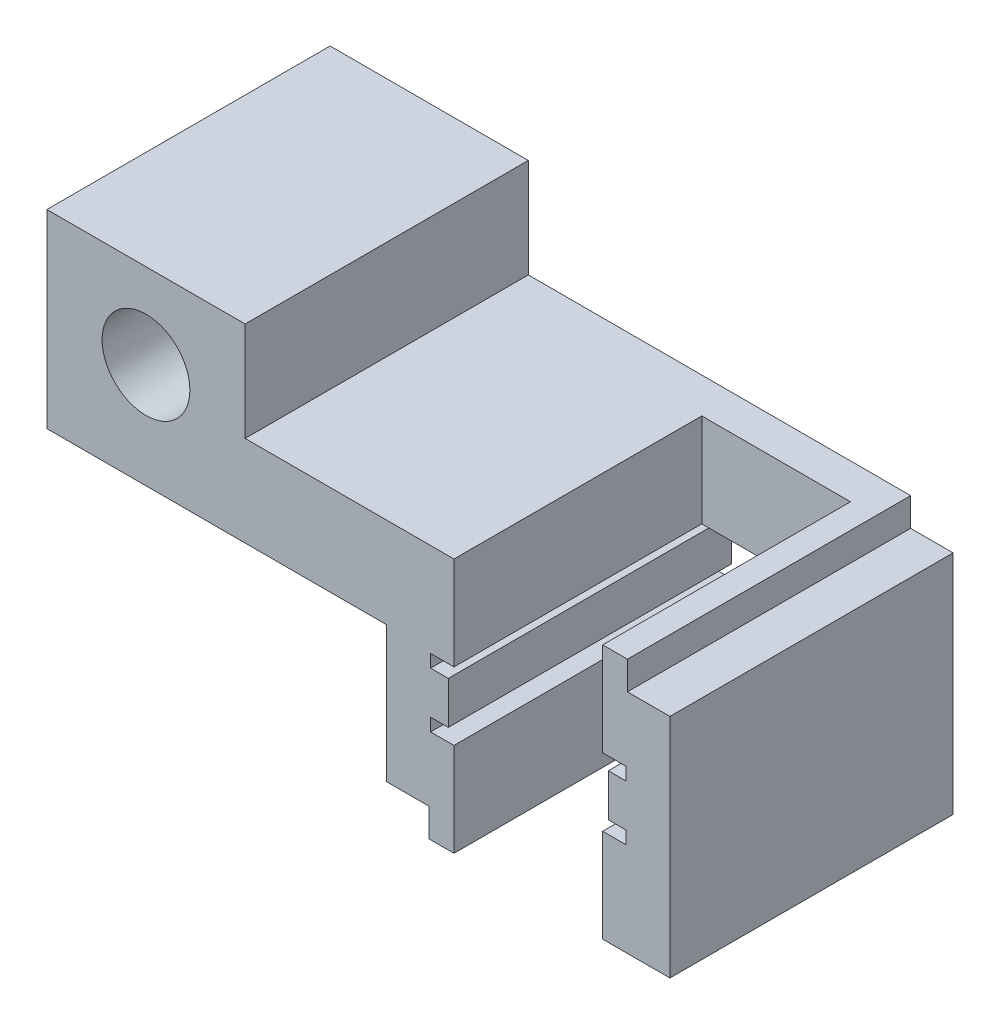
SolidWorks part; units mm, degrees
ref_plane "Front Plane" through (0, 0, 0) normal (0, 0, 1) x (1, 0, 0)
ref_plane "Top Plane" through (0, 0, 0) normal (0, 1, 0) x (1, 0, 0)
ref_plane "Right Plane" through (0, 0, 0) normal (1, 0, 0) x (0, 0, -1)
sketch "Sketch1" plane through (0, 0, 0) normal (0, 0, 1) x (1, 0, 0)
  line L1 (-9.5436, 2.8631) -> (10.4564, 2.8631)
  line L2 (-9.5436, 2.8631) -> (-9.5436, -0.1369)
  line L3 (-9.5436, -0.1369) -> (10.4564, -0.1369)
  line L4 (10.4564, 2.8631) -> (10.4564, -0.1369)
  dimension "D1" = 20
  dimension "D2" = 3
extrude "Boss-Extrude1" add sketch "Sketch1" against normal blind 20
sketch "Sketch2" plane through (0, 0, 0) normal (0, 0, 1) x (1, 0, 0)
  line L0 (0.4564, 2.8631) -> (0.4564, 1.802) construction
  line L1 (-5.1936, 2.8631) -> (6.1064, 2.8631)
  line L2 (-5.1936, 2.8631) -> (-5.1936, -0.1369)
  line L3 (-5.1936, -0.1369) -> (6.1064, -0.1369)
  line L4 (6.1064, 2.8631) -> (6.1064, -0.1369)
  line L5 (10.4564, 2.8631) -> (-9.5436, 2.8631) construction
  line L6 (-9.5436, -0.1369) -> (10.4564, -0.1369) construction
  point P8 (0.4564, 2.8631)
  dimension "D1" = 0
  dimension "D2" = 11.3
  dimension "D3" = 0
  dimension "D4" = 0
sketch "Sketch3" plane through (0, 0, 0) normal (0, 0, 1) x (1, 0, 0)
  line L0 (-9.5436, 2.8631) -> (-9.5436, -0.1369) construction
  line L1 (-9.5436, 10.3631) -> (10.4564, 10.3631)
  line L2 (-9.5436, 10.3631) -> (-9.5436, 2.8631)
  line L3 (-9.5436, 2.8631) -> (10.4564, 2.8631)
  line L4 (10.4564, 10.3631) -> (10.4564, 2.8631)
  dimension "D1" = 0
  dimension "D2" = 0
  dimension "D3" = 0
  dimension "D4" = 7.5
extrude "Boss-Extrude2" add sketch "Sketch3" against normal blind 20
sketch "Sketch4" plane through (0, 0, 0) normal (0, 0, 1) x (1, 0, 0)
  line L1 (-9.5436, -0.1369) -> (10.4564, -0.1369)
  line L2 (-9.5436, -0.1369) -> (-9.5436, -7.6369)
  line L3 (-9.5436, -7.6369) -> (10.4564, -7.6369)
  line L4 (10.4564, -0.1369) -> (10.4564, -7.6369)
  dimension "D1" = 0
  dimension "D2" = 0
  dimension "D3" = 0
  dimension "D4" = 7.5
extrude "Boss-Extrude3" add sketch "Sketch4" against normal blind 20
sketch "Sketch5" plane through (0, 0, 0) normal (0, 0, 1) x (1, 0, 0)
  line L0 (0.4564, -1.0369) -> (0.4564, -1.9441) construction
  line L1 (-6.4436, -0.1369) -> (7.3564, -0.1369)
  line L2 (-6.4436, -0.1369) -> (-6.4436, -1.0369)
  line L3 (-6.4436, -1.0369) -> (7.3564, -1.0369)
  line L4 (7.3564, -0.1369) -> (7.3564, -1.0369)
  line L5 (-5.1936, -0.1369) -> (6.1064, -0.1369) construction
  line L6 (0.4564, 3.7631) -> (0.4564, 5.897) construction
  line L7 (-6.4436, 3.7631) -> (7.3564, 3.7631)
  line L8 (-6.4436, 3.7631) -> (-6.4436, 2.8631)
  line L9 (-6.4436, 2.8631) -> (7.3564, 2.8631)
  line L10 (7.3564, 3.7631) -> (7.3564, 2.8631)
  line L11 (-5.1936, 2.8631) -> (6.1064, 2.8631) construction
  dimension "D1" = 0.9
  dimension "D2" = 13.8
  dimension "D3" = 0
  dimension "D4" = 0
  dimension "D5" = 13.8
  dimension "D6" = 0.9
  dimension "D7" = 0
  dimension "D8" = 0
sketch "Sketch6" plane through (0, 0, 0) normal (0, 0, 1) x (1, 0, 0)
  line L0 (10.4564, 10.3631) -> (-9.5436, 10.3631) construction
  line L1 (-4.7936, 10.3631) -> (5.7064, 10.3631)
  line L2 (-4.7936, 10.3631) -> (-4.7936, 3.7631)
  line L3 (-4.7936, 3.7631) -> (5.7064, 3.7631)
  line L4 (5.7064, 10.3631) -> (5.7064, 3.7631)
  line L5 (0.4564, 3.7631) -> (0.4564, 8.0136) construction
  line L6 (-6.4436, 3.7631) -> (7.3564, 3.7631) construction
  dimension "D1" = 10.5
  dimension "D2" = 0
  dimension "D3" = 0
  dimension "D4" = 0
sketch "Sketch7" plane through (0, 0, 0) normal (0, 0, 1) x (1, 0, 0)
  line L0 (0.4564, -7.6369) -> (0.4564, -4.6998) construction
  line L1 (-4.7936, -1.0369) -> (5.7064, -1.0369)
  line L2 (-4.7936, -1.0369) -> (-4.7936, -7.6369)
  line L3 (-4.7936, -7.6369) -> (5.7064, -7.6369)
  line L4 (5.7064, -1.0369) -> (5.7064, -7.6369)
  line L5 (-9.5436, -7.6369) -> (10.4564, -7.6369) construction
  line L6 (-6.4436, -1.0369) -> (7.3564, -1.0369) construction
  dimension "D1" = 10.5
  dimension "D2" = 0
  dimension "D3" = 0
  dimension "D4" = 0
extrude "Cut-Extrude1" cut sketch "Sketch2" against normal blind 20
extrude "Cut-Extrude2" cut sketch "Sketch5" against normal blind 20
extrude "Cut-Extrude3" cut sketch "Sketch6" against normal blind 17.5
extrude "Cut-Extrude4" cut sketch "Sketch7" against normal blind 17.5
sketch "Sketch8" plane through (0, 0, 0) normal (0, 0, 1) x (1, 0, 0)
  line L1 (10.4564, 10.3631) -> (7.4564, 10.3631)
  line L2 (10.4564, 10.3631) -> (10.4564, 8.3631)
  line L3 (10.4564, 8.3631) -> (7.4564, 8.3631)
  line L4 (7.4564, 10.3631) -> (7.4564, 8.3631)
  line L5 (-9.5436, -7.6369) -> (-6.5436, -7.6369)
  line L6 (-9.5436, -7.6369) -> (-9.5436, -5.6369)
  line L7 (-9.5436, -5.6369) -> (-6.5436, -5.6369)
  line L8 (-6.5436, -7.6369) -> (-6.5436, -5.6369)
  dimension "D1" = 2
  dimension "D2" = 3
  dimension "D3" = 2
  dimension "D4" = 3
extrude "Cut-Extrude5" cut sketch "Sketch8" against normal blind 20
sketch "Sketch9" plane through (-9.5436, 0, 0) normal (-1, 0, 0) x (0, 0, 1)
  line L0 (-20, 10.3631) -> (-20, -5.6369) construction
  line L1 (-20, 17.3631) -> (0, 17.3631)
  line L2 (-20, 17.3631) -> (-20, 3.9631)
  line L3 (-20, 3.9631) -> (0, 3.9631)
  line L4 (0, 17.3631) -> (0, 3.9631)
  line L5 (0, 10.3631) -> (0, -5.6369) construction
  line L6 (-20, 10.3631) -> (0, 10.3631) construction
  dimension "D1" = 13.4
  dimension "D2" = 0
  dimension "D3" = 0
  dimension "D4" = 6.4
extrude "Boss-Extrude4" add sketch "Sketch9" along normal blind 24
sketch "Sketch10" plane through (0, 0, 0) normal (0, 0, 1) x (1, 0, 0)
  circle A0 centre (-26.5436, 11.3631) radius 3.1
  dimension "D1" = 6.2
  dimension "D2" = 6
  dimension "D3" = 7
sketch "Sketch11" plane through (0, 0, 0) normal (0, 0, 1) x (1, 0, 0)
  circle A0 centre (-26.5436, 11.3631) radius 1.45
  dimension "D1" = 2.9
extrude "Cut-Extrude6" cut sketch "Sketch10" against normal blind 19
extrude "Cut-Extrude7" cut sketch "Sketch11" against normal blind 20
sketch "Sketch12" plane through (0, 0, 0) normal (0, 0, 1) x (1, 0, 0)
  line L1 (-9.5436, 17.3631) -> (-19.5436, 17.3631)
  line L2 (-9.5436, 17.3631) -> (-9.5436, 10.3631)
  line L3 (-9.5436, 10.3631) -> (-19.5436, 10.3631)
  line L4 (-19.5436, 17.3631) -> (-19.5436, 10.3631)
  dimension "D1" = 0
  dimension "D2" = 10
extrude "Cut-Extrude8" cut sketch "Sketch12" against normal blind 20
